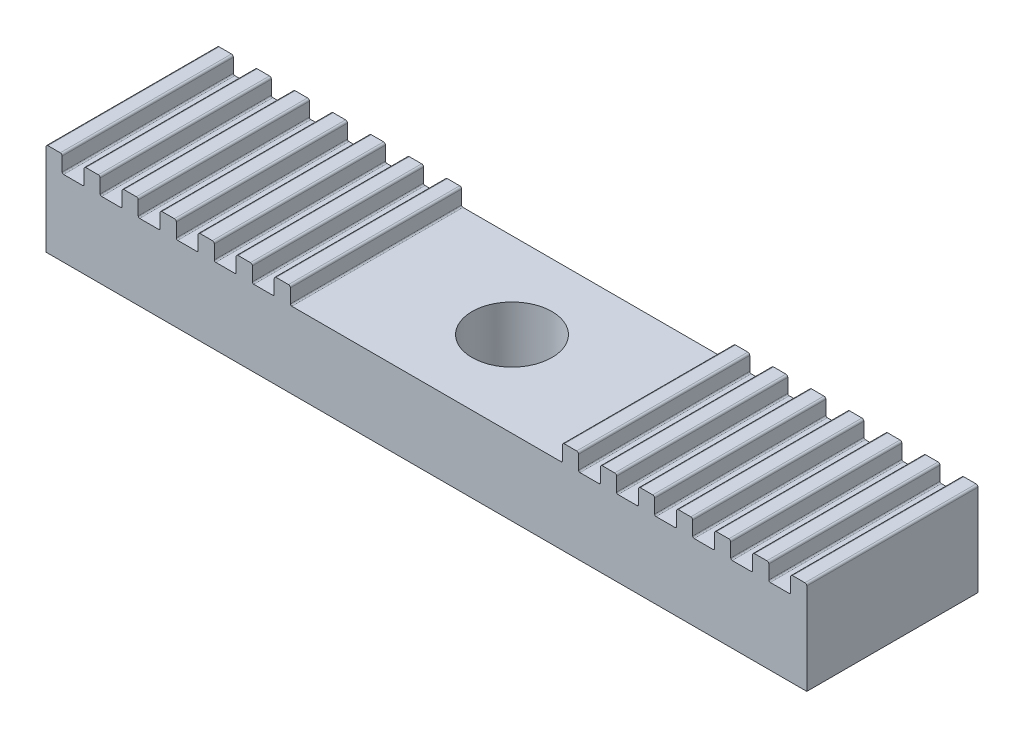
SolidWorks part; units mm, degrees
material "6061-T6 (SS)"
ref_plane "Front Plane" through (0, 0, 0) normal (0, 0, 1) x (1, 0, 0)
ref_plane "Top Plane" through (0, 0, 0) normal (0, 1, 0) x (1, 0, 0)
ref_plane "Right Plane" through (0, 0, 0) normal (1, 0, 0) x (0, 0, -1)
sketch "BaseS" plane through (0, 0, 0) normal (0, 1, 0) x (1, 0, 0)
  line L1 (-20, 4.5) -> (20, 4.5)
  line L2 (-20, 4.5) -> (-20, -4.5)
  line L3 (-20, -4.5) -> (20, -4.5)
  line L4 (20, 4.5) -> (20, -4.5)
  line L5 (-20, 4.5) -> (20, -4.5) construction
  line L6 (-20, -4.5) -> (20, 4.5) construction
  point P0 (0, 0)
  dimension "Width" = 9
  dimension "Length" = 40
extrude "Base" add sketch "BaseS" along normal blind 4
sketch "ToothProfileNestWallS" plane through (0, 0, 0) normal (0, 0, 1) x (1, 0, 0)
  line L0 (-19.075, 4) -> (-20.075, 4)
  line L1 (-20, 4) -> (20, 4) construction
  line L2 (-20, 4.075) -> (-20, 4.8)
  line L3 (-19.9, 4.9) -> (-19.25, 4.9)
  line L4 (-19.15, 4.075) -> (-19.15, 4.8)
  line L5 (-19.575, 4) -> (-19.575, 4.9) construction
  line L6 (-20, 4.075) -> (-20, 4) construction
  arc A0 (-20.075, 4) -> (-20, 4.075) centre (-20.075, 4.075) ccw
  arc A1 (-19.9, 4.9) -> (-20, 4.8) centre (-19.9, 4.8) ccw
  arc A2 (-19.25, 4.9) -> (-19.15, 4.8) centre (-19.25, 4.8) cw
  arc A3 (-19.075, 4) -> (-19.15, 4.075) centre (-19.075, 4.075) cw
  dimension "R2" = 0.1
  dimension "D1" = 0.85
  dimension "Height" = 0.9
  dimension "RefTopWidth" = 0.85
  dimension "TopWidthControl" = 0.075
extrude "ToothProfileNestWall" add sketch "ToothProfileNestWallS" along normal up to surface and the other way up to surface up to face at (0, 2, 4.5) other way up to face at (0, 2, -4.5)
pattern_linear "TPNWLP" count 7 spacing 2 along (1, 0, 0) of "ToothProfileNestWall"
sketch "TPFilletCutS" plane through (0, 0, 0) normal (0, 0, 1) x (1, 0, 0)
  line L0 (-20, 4) -> (-20, 0) construction
  line L1 (-20.075, 4) -> (-20, 4)
  line L2 (-20.075, 4) -> (-20.075, 4.075)
  line L3 (-20.075, 4.075) -> (-20, 4.075)
  line L5 (-20, 4.075) -> (-20, 4.8) construction
  line L6 (-20, 4) -> (-20, 4.075)
extrude "TPFilletCut" cut sketch "TPFilletCutS" against normal through all both and the other way through all
mirror "TPNWSetHM" about plane through (0, 0, 0) normal (1, 0, 0) of "TPFilletCut", "ToothProfileNestWall", "TPNWLP"
hole_wizard "M4 Clearance Hole1" positions "Sketch3" profile "Sketch4" hole size "M4" standard "ANSI Metric" end condition through all
sketch "Sketch3" plane through (0, 0, 0) normal (0, -1, 0) x (-1, 0, 0)
  point P0 (0, 0)
sketch "Sketch4" plane through (0, 0, 0) normal (1, 0, 0) x (0, 0, -1)
  line L0 (0, 0) -> (0, 4.9)
  line L1 (0, 4.9) -> (2.1, 4.9)
  line L2 (2.1, 4.9) -> (2.1, 0.15)
  line L3 (2.1, 0.15) -> (2.25, 0)
  line L5 (2.25, 0) -> (0, 0)
  line L6 (-2.1, 0.15) -> (-2.25, 0) construction
  line L11 (0, -6.35) -> (0, 107.95) construction
  dimension "Thru Hole Dia." = 4.2
  dimension "Thru Hole Depth" = 4.9
  dimension "Near C'Sink Dia." = 4.5
  dimension "Near C'Sink Angle" = 90
